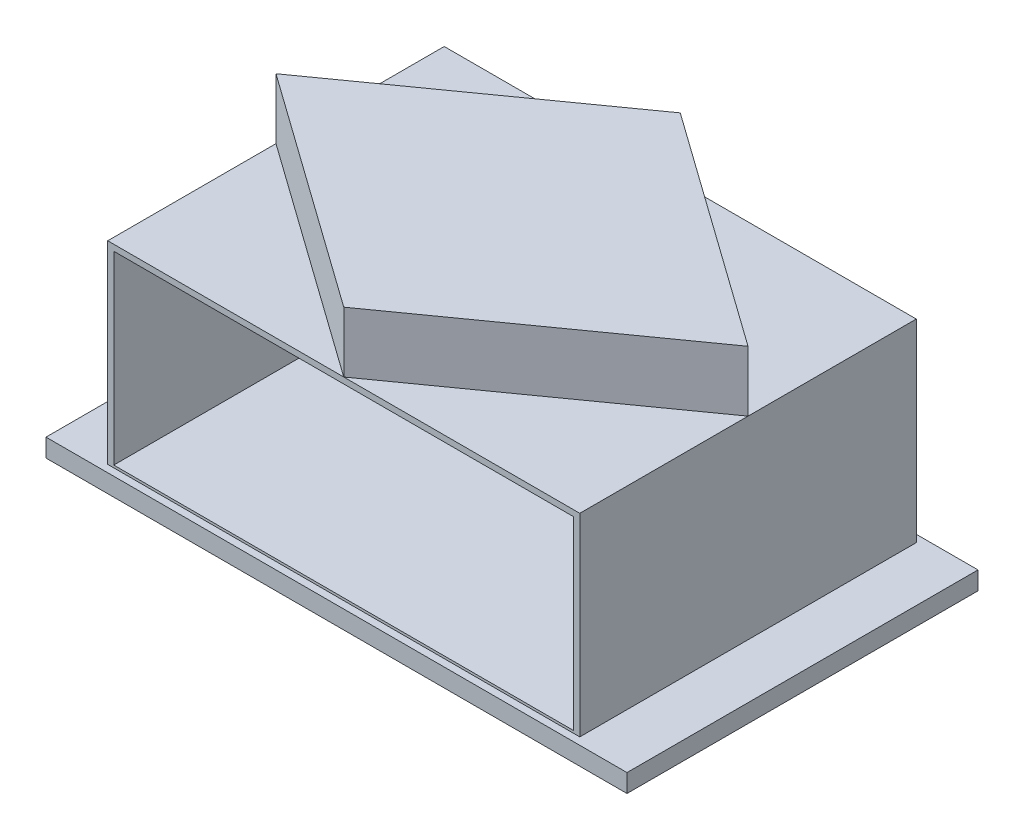
SolidWorks part; units mm, degrees
ref_plane "前视基准面" through (0, 0, 0) normal (0, 0, 1) x (1, 0, 0)
ref_plane "上视基准面" through (0, 0, 0) normal (0, 1, 0) x (1, 0, 0)
ref_plane "右视基准面" through (0, 0, 0) normal (1, 0, 0) x (0, 0, -1)
other "Configuration Table"
sketch "草图1" plane through (0, 0, 0) normal (0, 1, 0) x (1, 0, 0)
  line L1 (-240, -145) -> (240, -145)
  line L2 (-240, -145) -> (-240, 145)
  line L3 (-240, 145) -> (240, 145)
  line L4 (240, -145) -> (240, 145)
  line L5 (-240, -145) -> (240, 145) construction
  line L6 (-240, 145) -> (240, -145) construction
  point P0 (0, 0)
extrude "凸台-拉伸1" add sketch "草图1" against normal blind 15
sketch "草图2" plane through (0, 0, 0) normal (0, 1, 0) x (1, 0, 0)
  line L1 (-195, -39) -> (195, -39)
  line L2 (-195, -39) -> (-195, 139)
  line L3 (-195, 139) -> (195, 139)
  line L4 (195, -39) -> (195, 139)
  line L5 (-195, -39) -> (195, 139) construction
  line L6 (-195, 139) -> (195, -39) construction
  point P0 (0, 50)
extrude "凸台-拉伸2" add sketch "草图2" along normal blind 160
sketch "草图7" plane through (0, 0, 39) normal (0, 0, 1) x (1, 0, 0)
  line L0 (-195, 160) -> (-195, 0)
  line L1 (-195, 0) -> (195, 0)
  line L2 (195, 0) -> (195, 160)
  line L3 (195, 160) -> (-195, 160)
extrude "凸台-拉伸7" add sketch "草图7" along normal blind 100
sketch "草图8" plane through (0, 0, 139) normal (0, 0, 1) x (1, 0, 0)
  line L0 (-190, 155) -> (190, 155)
  line L1 (190, 155) -> (190, 2)
  line L2 (190, 2) -> (-190, 2)
  line L3 (-190, 2) -> (-190, 155)
  line L4 (-195, 0) -> (195, 0) construction
  line L5 (-195, 160) -> (-195, 0) construction
  line L6 (195, 0) -> (195, 160) construction
  line L7 (195, 160) -> (-195, 160) construction
  dimension "D1" = 2
  dimension "D2" = 5
  dimension "D3" = 5
  dimension "D4" = 5
extrude "切除-拉伸1" cut sketch "草图8" against normal blind 240
sketch "草图10" plane through (0, 160, 0) normal (0, 1, 0) x (1, 0, 0)
  line L0 (0, 139) -> (-195, 0)
  line L1 (195, 139) -> (-195, 139) construction
  line L2 (-195, 139) -> (-195, -139) construction
  line L3 (-195, 0) -> (0, -139)
  line L4 (195, -139) -> (-195, -139) construction
  line L5 (0, -139) -> (195, 0)
  line L6 (195, -139) -> (195, 139) construction
  line L7 (195, 0) -> (0, 139)
extrude "凸台-拉伸8" add sketch "草图10" along normal blind 50
